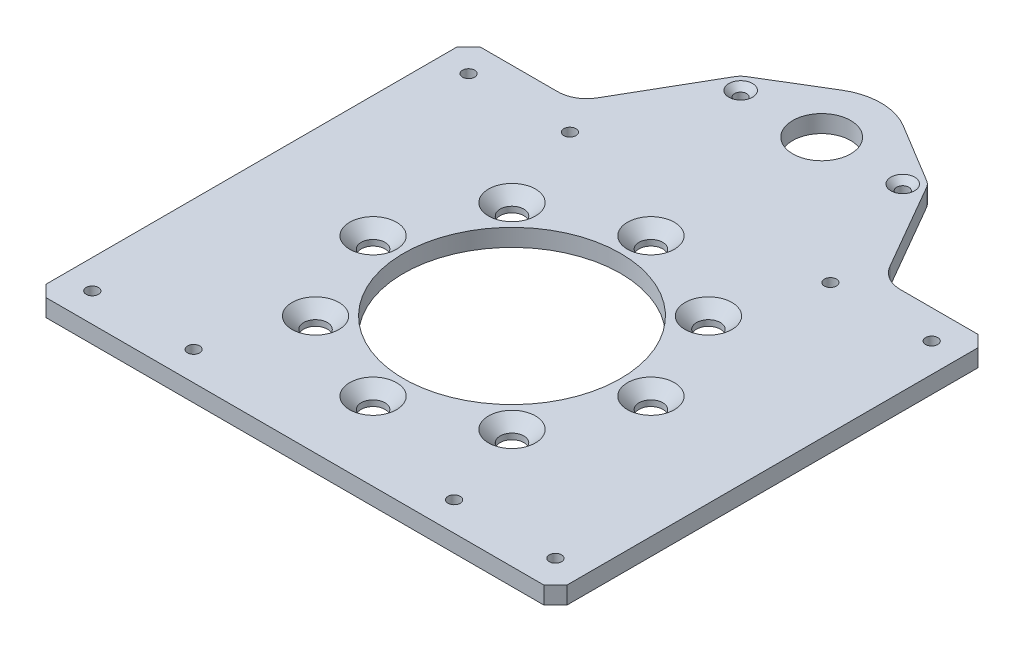
SolidWorks part; units mm, degrees
ref_plane "前视基准面" through (0, 0, 0) normal (0, 0, 1) x (1, 0, 0)
ref_plane "上视基准面" through (0, 0, 0) normal (0, 1, 0) x (1, 0, 0)
ref_plane "右视基准面" through (0, 0, 0) normal (1, 0, 0) x (0, 0, -1)
sketch "草图1" plane through (0, 0, 0) normal (0, 1, 0) x (1, 0, 0)
  line L0 (0, 75) -> (0, -75) construction
  line L1 (-90, 75) -> (90, 75)
  line L2 (-90, 75) -> (-90, -75)
  line L3 (-90, -75) -> (90, -75)
  line L4 (90, 75) -> (90, -75)
  line L5 (-90, 75) -> (90, -75) construction
  line L6 (-90, -75) -> (90, 75) construction
  line L7 (-90, 0) -> (90, 0) construction
  line L8 (-80, 65) -> (-45, 65) construction
  circle A0 centre (0, 0) radius 48 construction
  circle A1 centre (0, 48) radius 4.1
  circle A2 centre (33.9411, 33.9411) radius 4.1
  circle A3 centre (48, 0) radius 4.1
  circle A4 centre (33.9411, -33.9411) radius 4.1
  circle A5 centre (0, -48) radius 4.1
  circle A6 centre (-33.9411, -33.9411) radius 4.1
  circle A7 centre (-48, 0) radius 4.1
  circle A8 centre (-33.9411, 33.9411) radius 4.1
  circle A11 centre (-80, 65) radius 2.1
  circle A12 centre (-45, 65) radius 2.1
  circle A13 centre (45, 65) radius 2.1
  circle A14 centre (80, 65) radius 2.1
  circle A15 centre (80, -65) radius 2.1
  circle A16 centre (45, -65) radius 2.1
  circle A17 centre (-45, -65) radius 2.1
  circle A18 centre (-80, -65) radius 2.1
  point P0 (0, 0)
  dimension "D2" = 96
  dimension "D3" = 8.2
  dimension "D5" = 35
  dimension "D6" = 4.2
  dimension "D8" = 10
  dimension "D7" = 10
  dimension "D1" = 180
  dimension "D9" = 150
  dimension "D4" = 8
extrude "凸台-拉伸1" add sketch "草图1" along normal mid plane 6
chamfer "倒角1" distance 4 angle 45 8 edges at (-48, 3, 4.1) (-33.9411, 3, -29.8411) (0, 3, -43.9) (33.9411, 3, -29.8411) (48, 3, 4.1) (33.9411, 3, 38.0411) (0, 3, 52.1) (-33.9411, 3, 38.0411)
chamfer "倒角2" distance 4 angle 45 4 edges at (-90, 0, -75) (90, 0, -75) (90, 0, 75) (-90, 0, 75)
chamfer "倒角3" distance 2 angle 45 8 edges at (45, -3, 67.1) (45, -3, -67.1) (-45, -3, -62.9) (-45, -3, 62.9) (80, -3, -67.1) (-80, -3, 62.9) (80, -3, 67.1) (-80, -3, -62.9)
sketch "草图3" plane through (0, -3, 0) normal (0, -1, 0) x (1, 0, 0)
  circle A0 centre (0, 0) radius 37.5
  dimension "D1" = 75
extrude "切除-拉伸1" cut sketch "草图3" against normal through all
sketch "草图4" plane through (0, -3, 0) normal (0, -1, 0) x (1, 0, 0)
  line L0 (28, -107) -> (-28, -107) construction
  line L1 (-31.1071, -112.1328) -> (-10.6161, -124.5371)
  line L2 (10.6161, -124.5371) -> (31.1071, -112.1328)
  line L3 (-33.1962, -110) -> (-53.4034, -75)
  line L4 (86, -75) -> (-86, -75) construction
  line L5 (33.1962, -110) -> (53.4034, -75)
  line L6 (-53.4034, -75) -> (53.4034, -75)
  circle A1 centre (-28, -107) radius 2.1
  circle A2 centre (28, -107) radius 2.1
  arc A3 (-33.1962, -110) -> (-31.1071, -112.1328) centre (-28, -107) ccw
  arc A4 (31.1071, -112.1328) -> (33.1962, -110) centre (28, -107) ccw
  arc A5 (-10.6161, -124.5371) -> (10.6161, -124.5371) centre (0, -107) ccw
  circle A6 centre (0, -107) radius 10
  point P8 (0, -107)
  dimension "D1" = 107
  dimension "D2" = 4.2
  dimension "D4" = 41
  dimension "D5" = 12
  dimension "D6" = 20
  dimension "D3" = 56
  dimension "D8" = 60
extrude "凸台-拉伸2" add sketch "草图4" against normal blind 6
chamfer "倒角4" distance 2 angle 45 2 edges at (28, 3, -109.1) (-28, 3, -109.1)
fillet "圆角1" radius 10 2 edges at (53.4034, 0, -75) (-53.4034, 0, -75)
